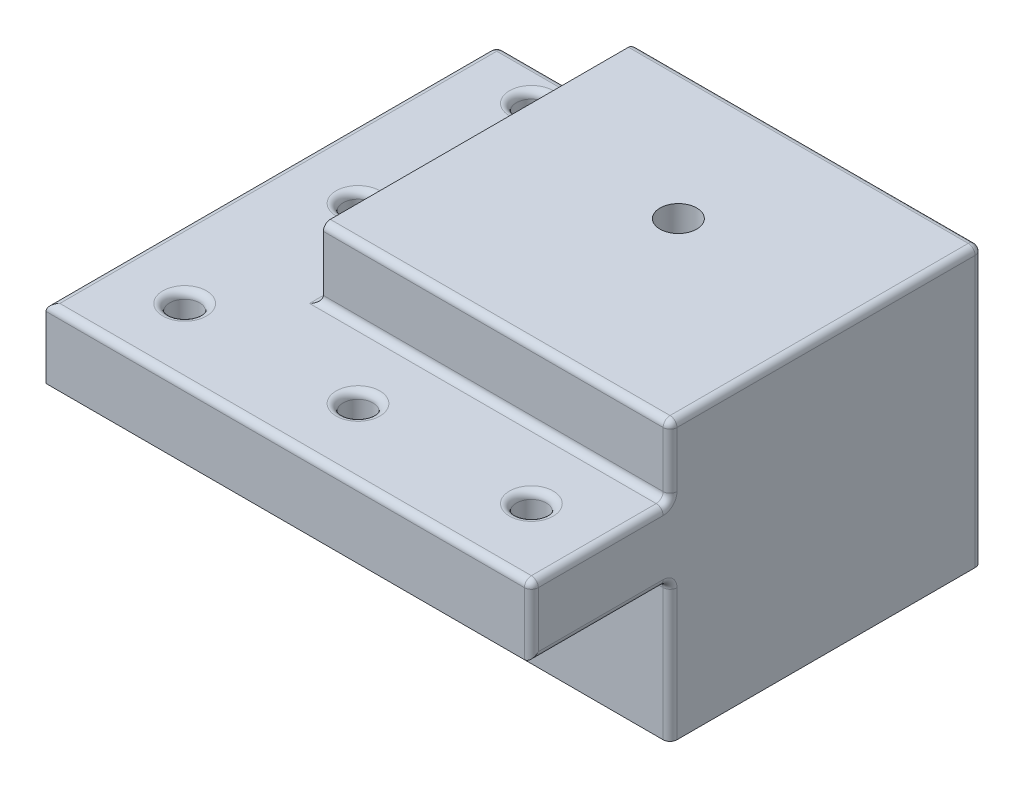
SolidWorks part; units mm, degrees
material "PLA"
ref_plane "前视基准面" through (0, 0, 0) normal (0, 0, 1) x (1, 0, 0)
ref_plane "上视基准面" through (0, 0, 0) normal (0, 1, 0) x (1, 0, 0)
ref_plane "右视基准面" through (0, 0, 0) normal (1, 0, 0) x (0, 0, -1)
sketch "草图1" plane through (0, 0, 0) normal (0, 0, 1) x (1, 0, 0)
  line L0 (0, 0) -> (0, -74.9741) construction
  line L1 (25, 0) -> (-25, 0)
  line L2 (-25, 0) -> (-25, -10)
  line L3 (-25, -10) -> (-80, -10)
  line L4 (-80, -10) -> (-80, -20)
  line L5 (-80, -20) -> (-60, -20)
  line L6 (-60, -20) -> (-60, -40)
  line L7 (-60, -40) -> (60, -40)
  line L8 (60, -20) -> (60, -40)
  line L9 (80, -20) -> (60, -20)
  line L10 (25, -10) -> (80, -10)
  line L11 (25, 0) -> (25, -10)
  line L12 (80, -10) -> (80, -20)
  point P11 (0, -40)
  dimension "D1" = 160
  dimension "D2" = 120
  dimension "D3" = 50
  dimension "D4" = 40
  dimension "D5" = 20
  dimension "D6" = 10
extrude "凸台-拉伸1" add sketch "草图1" along normal blind 45
sketch "草图2" plane through (0, 0, 0) normal (0, 0, -1) x (-1, 0, 0)
  line L0 (60, -40) -> (-60, -40) construction
  line L1 (-15, -40) -> (15, -40)
  line L2 (-15, -40) -> (-15, -5)
  line L3 (-15, -5) -> (15, -5)
  line L4 (15, -40) -> (15, -5)
  line L5 (0, -5) -> (0, -40) construction
  line L6 (-15, -22.5) -> (15, -22.5) construction
  point P72 (0, -22.5)
  dimension "D1" = 30
  dimension "D2" = 35
extrude "切除-拉伸1" cut sketch "草图2" against normal blind 40.5
sketch "草图4" plane through (0, -5, 0) normal (0, -1, 0) x (1, 0, 0)
  line L0 (0, 0) -> (0, 34.7086) construction
  line L1 (15, 40.5) -> (-15, 40.5) construction
  circle A0 centre (0, 18.8) radius 2.65
  dimension "D1" = 5.3
  dimension "D2" = 21.7
extrude "切除-拉伸2" cut sketch "草图4" against normal blind 40
sketch "草图6" plane through (0, -10, 0) normal (0, 1, 0) x (1, 0, 0)
  line L0 (70, 0) -> (70, -45) construction
  line L1 (80, 0) -> (25, 0) construction
  line L2 (80, -45) -> (25, -45) construction
  line L3 (0, 0) -> (0, -83.6514) construction
  line L4 (80, -45) -> (80, 0) construction
  line L5 (80, -22.5) -> (37.0042, -22.5) construction
  circle A0 centre (70, -10) radius 2.65
  circle A1 centre (70, -35) radius 2.65
  circle A2 centre (-70, -35) radius 2.65
  circle A3 centre (-70, -10) radius 2.65
  dimension "D2" = 25
  dimension "D3" = 5.3
  dimension "D1" = 10
extrude "切除-拉伸4" cut sketch "草图6" against normal through all
sketch "草图7" plane through (0, -10, 0) normal (0, 1, 0) x (1, 0, 0)
  line L0 (-25, -45) -> (-25, 0) construction
  line L1 (-80, 0) -> (-25, 0)
  line L2 (-80, 0) -> (-80, -3)
  line L3 (-80, -3) -> (-25, -3)
  line L4 (-25, 0) -> (-25, -3)
  line L5 (-52.5, -3) -> (-52.5, 0) construction
  line L6 (-80, -1.5) -> (-25, -1.5) construction
  line L7 (0, 21.4981) -> (0, -18.8) construction
  line L8 (-80, -22.5) -> (33.6156, -22.5) construction
  line L9 (-80, -45) -> (-80, 0) construction
  line L10 (-80, -42) -> (-25, -42)
  line L11 (-25, -45) -> (-25, -42)
  line L12 (-80, -45) -> (-25, -45)
  line L13 (-80, -45) -> (-80, -42)
  line L14 (80, -45) -> (80, -42)
  line L15 (80, -45) -> (25, -45)
  line L16 (25, -45) -> (25, -42)
  line L17 (80, -42) -> (25, -42)
  line L18 (80, -3) -> (25, -3)
  line L19 (25, 0) -> (25, -3)
  line L20 (80, 0) -> (25, 0)
  line L21 (80, 0) -> (80, -3)
  point P128 (-52.5, -1.5)
  dimension "D1" = 3
extrude "切除-拉伸5" cut sketch "草图7" against normal through all
sketch "草图8" plane through (0, -10, 0) normal (0, 1, 0) x (1, 0, 0)
  line L0 (0, 0) -> (0, -56.9029) construction
  line L1 (-80, -3) -> (-25, -3)
  line L2 (-80, -3) -> (-80, -42)
  line L3 (-80, -42) -> (-25, -42)
  line L4 (-25, -3) -> (-25, -42)
  line L5 (-52.5, -42) -> (-52.5, -3) construction
  line L6 (-80, -22.5) -> (-25, -22.5) construction
  line L7 (25, 0) -> (-25, 0) construction
  line L8 (80, -22.5) -> (25, -22.5) construction
  line L9 (52.5, -42) -> (52.5, -3) construction
  line L10 (25, -3) -> (25, -42)
  line L11 (80, -42) -> (25, -42)
  line L12 (80, -3) -> (80, -42)
  line L13 (80, -3) -> (25, -3)
  point P18 (52.5, -22.5)
  point P172 (-52.5, -22.5)
extrude "切除-拉伸6" cut sketch "草图8" against normal through all
sketch "草图9" plane through (0, 0, 0) normal (0, 1, 0) x (1, 0, 0)
  line L0 (-35, -45) -> (-35, -65) construction
  line L1 (-25, 0) -> (-45, 0)
  line L2 (-25, 0) -> (-25, -45)
  line L3 (-25, -45) -> (-45, -45)
  line L4 (-45, 0) -> (-45, -45)
  line L5 (-35, -45) -> (-35, 0) construction
  line L6 (-25, -22.5) -> (-45, -22.5) construction
  line L7 (25, -45) -> (-45, -45)
  line L8 (25, -45) -> (25, -65)
  line L9 (25, -65) -> (-45, -65)
  line L10 (-45, -45) -> (-45, -65)
  line L11 (-10, -65) -> (-10, -45) construction
  line L12 (25, -55) -> (-45, -55) construction
  circle A0 centre (-35, -55) radius 2.15
  circle A1 centre (-35, -30) radius 2.15
  circle A2 centre (-35, -5) radius 2.15
  circle A3 centre (-10, -55) radius 2.15
  circle A4 centre (15, -55) radius 2.15
  point P104 (-35, -22.5)
  point P142 (-10, -55)
  line M10 (-25, 0) -> (-25, -45)
  line M11 (-25, -45) -> (25, -45)
  dimension "D3" = 25
  dimension "D4" = 25
  dimension "D5" = 25
  dimension "D6" = 25
  dimension "D7" = 4.3
  dimension "D1" = 20
  dimension "D2" = 20
extrude "凸台-拉伸2" add sketch "草图9" against normal blind 20 contours L3 L10 L9 L8 A4 A3 A0 M11 | L1 L4 L3 A2 A1 M10
sketch "草图10" plane through (0, 0, 0) normal (0, 1, 0) x (1, 0, 0)
  line L0 (-45, 0) -> (-45, -65) construction
  line L1 (25, 0) -> (-25, 0)
  line L2 (25, 0) -> (25, -45)
  line L3 (25, -45) -> (-25, -45)
  line L4 (-25, 0) -> (-25, -45)
  line L5 (0, -45) -> (0, 0) construction
  line L6 (25, -22.5) -> (-25, -22.5) construction
  line L7 (25, -65) -> (-45, -65) construction
  point P128 (0, -22.5)
  dimension "D1" = 20
  dimension "D2" = 20
extrude "切除-拉伸7" cut sketch "草图10" against normal blind 10 flip side to cut
fillet "圆角1" radius 1 26 edges at (25, -30, 45) (-25, -30, 0) (25, -5, 45) (-25, -5, 0) (25, 0, 22.5) (25, -20, 0) (-25, -30, 45) (-35, -10, 32.15) (15, -10, 57.15) (-10, -10, 57.15) (-35, -10, 57.15) (-35, -10, 7.15) (0, -20, 45) (-25, -20, 22.5) (-35, -20, 0) (25, -20, 55) (25, -15, 65) (-45, -15, 0) (-10, -10, 65) (-45, -10, 32.5) (25, -10, 55) (-25, -10, 22.5) (0, -10, 45) (-35, -10, 0) (0, 0, 0) (0, 0, 45)
